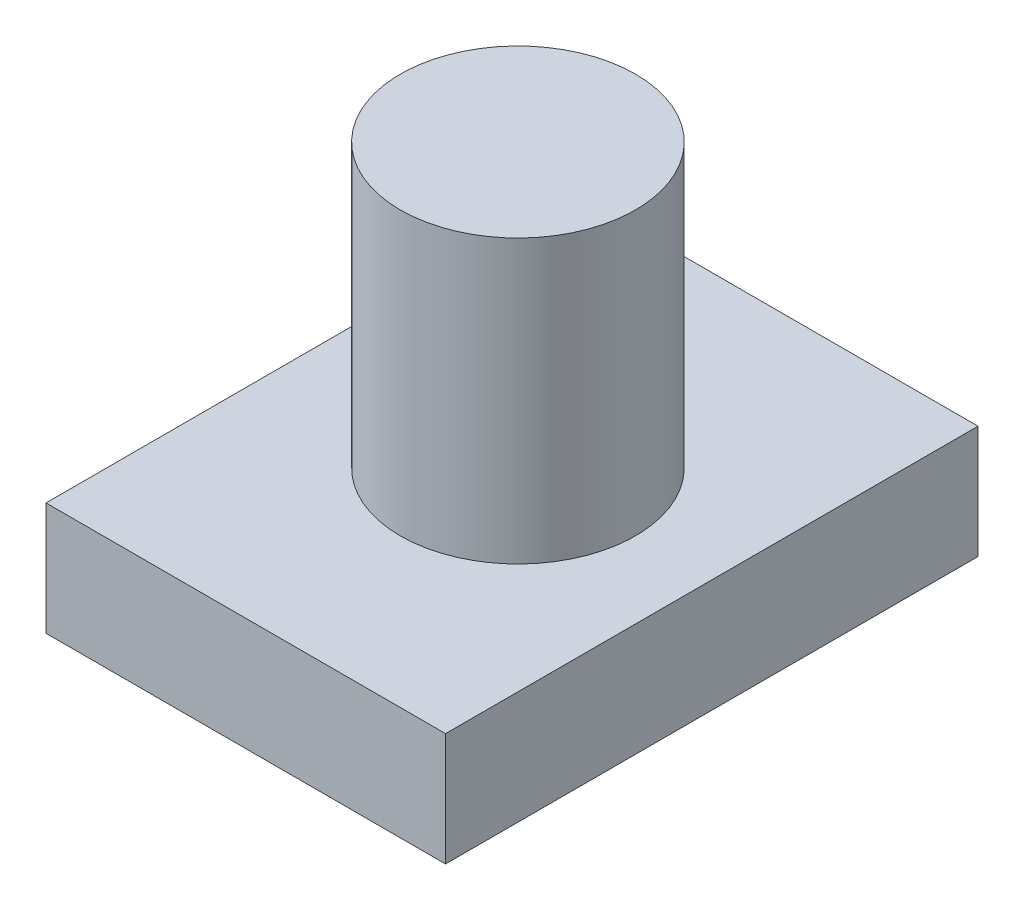
SolidWorks part; units mm, degrees
ref_plane "Спереди" through (0, 0, 0) normal (0, 0, 1) x (1, 0, 0)
ref_plane "Сверху" through (0, 0, 0) normal (0, 1, 0) x (1, 0, 0)
ref_plane "Справа" through (0, 0, 0) normal (1, 0, 0) x (0, 0, -1)
sketch "Эскиз1" plane through (0, 0, 0) normal (0, 1, 0) x (1, 0, 0)
  circle A0 centre (0, 0) radius 12.5
extrude "Вытянуть1" add sketch "Эскиз1" along normal blind 30
sketch "Эскиз2" plane through (0, 0, 0) normal (0, -1, 0) x (1, 0, 0)
  line L1 (-21.8583, -28.2931) -> (20.6034, -28.2931)
  line L2 (-21.8583, -28.2931) -> (-21.8583, 28.2931)
  line L3 (-21.8583, 28.2931) -> (20.6034, 28.2931)
  line L4 (20.6034, -28.2931) -> (20.6034, 28.2931)
  line L5 (-21.8583, -28.2931) -> (20.6034, 28.2931) construction
  line L6 (-21.8583, 28.2931) -> (20.6034, -28.2931) construction
extrude "Вытянуть2" add sketch "Эскиз2" along normal blind 12
